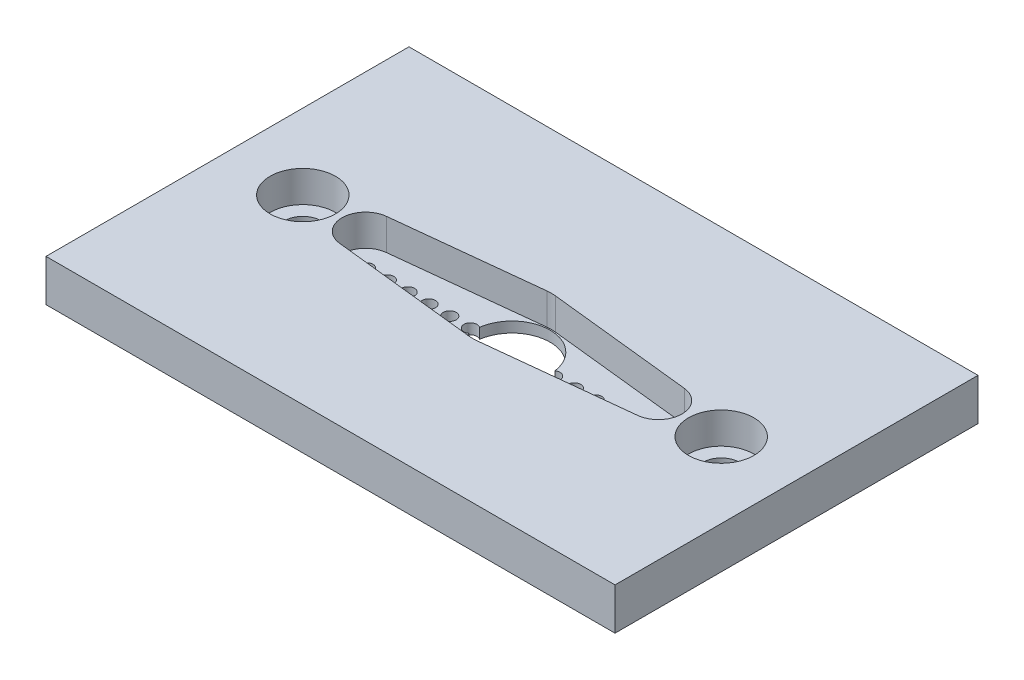
SolidWorks part; units mm, degrees
material "PLA"
ref_plane "Front Plane" through (0, 0, 0) normal (0, 0, 1) x (1, 0, 0)
ref_plane "Top Plane" through (0, 0, 0) normal (0, 1, 0) x (1, 0, 0)
ref_plane "Right Plane" through (0, 0, 0) normal (1, 0, 0) x (0, 0, -1)
sketch "Sketch1" plane through (0, 0, 0) normal (0, 1, 0) x (1, 0, 0)
  line L1 (-27.2, -17.35) -> (27.2, -17.35)
  line L2 (-27.2, -17.35) -> (-27.2, 17.35)
  line L3 (-27.2, 17.35) -> (27.2, 17.35)
  line L4 (27.2, -17.35) -> (27.2, 17.35)
  line L5 (-27.2, -17.35) -> (27.2, 17.35) construction
  line L6 (-27.2, 17.35) -> (27.2, -17.35) construction
  point P0 (0, 0)
  dimension "D1" = 34.7
  dimension "D2" = 54.4
extrude "Boss-Extrude1" add sketch "Sketch1" along normal blind 4
sketch "Sketch2" plane through (0, 4, 0) normal (0, 1, 0) x (1, 0, 0)
  line L0 (-27.2, -17.35) -> (-27.2, 0) construction
  line L2 (-27.2, 17.35) -> (-27.2, -17.35) construction
  line L3 (-27.2, 0) -> (-23.125, 0) construction
  line L4 (-23.125, 0) -> (-23.125, 3.0275) construction
  line L5 (-23.125, 3.0275) -> (-19.2256, 3.0275) construction
  line L6 (-23.125, 0) -> (-23.125, -3.0275) construction
  line L7 (-23.125, -3.0275) -> (-19.2256, -3.0275) construction
  line L8 (0, -55) -> (0, 55) construction
  circle A4 centre (-20, 0) radius 3.125
  circle A5 centre (20, 0) radius 3.125
  dimension "D1" = 4.075
  dimension "D2" = 17.35
  dimension "D3" = 3.0275
  dimension "D4" = 3.8994
  dimension "D5" = 3.8994
  dimension "D6" = 3.0275
extrude "Cut-Extrude1" cut sketch "Sketch2" against normal blind 3
sketch "Sketch7" plane through (0, 1, 0) normal (0, 1, 0) x (1, 0, 0)
  line L0 (0, -2.2) -> (0, 2.2) construction
  circle A0 centre (-20, 0) radius 1.75
  circle A1 centre (20, 0) radius 1.75
extrude "Cut-Extrude5" cut sketch "Sketch7" against normal through all
sketch "Sketch8" plane through (0, 4, 0) normal (0, 1, 0) x (1, 0, 0)
  line L0 (0, 18.9925) -> (0, -21.0066) construction
  line L1 (-3.971, 0.6223) -> (-5.9596, 0.6212) construction
  line L2 (-4.0428, 0) -> (-4.0428, 0.6182) construction
  line L3 (-4.0428, 0.6182) -> (-4.0428, -0.5248) construction
  line L4 (-4.0428, -0.5248) -> (-3.6366, -0.5248) construction
  line L5 (-4.0428, 0.6182) -> (-4.0428, -0.2735) construction
  line L6 (-4.0428, -0.2735) -> (-4.5299, -0.2735) construction
  line L7 (-5.9596, -0.6223) -> (-3.971, -0.6223) construction
  line L8 (-5.3378, -0.0014) -> (-5.9596, 0.6212) construction
  line L9 (-5.9596, 0.6212) -> (-6.5712, -0.1123) construction
  line L10 (5.9596, 0.6212) -> (6.5712, -0.1123) construction
  line L11 (5.3378, -0.0014) -> (5.9596, 0.6212) construction
  line L12 (5.9596, -0.6223) -> (3.971, -0.6223) construction
  line L13 (4.0428, -0.2735) -> (4.5299, -0.2735) construction
  line L14 (3.971, 0.6223) -> (5.9596, 0.6212) construction
  line L15 (0, 0) -> (3.971, 0) construction
  line L16 (4.0428, 0) -> (5.9596, -0.0005) construction
  line L17 (4.0428, 0) -> (5.9596, 0) construction
  line L18 (5.9596, 0) -> (7.9482, 0) construction
  line L19 (7.9482, 0) -> (9.9368, -0.0005) construction
  line L20 (9.9368, -0.0005) -> (11.9254, 0) construction
  line L21 (11.9254, 0) -> (13.914, -0.0005) construction
  arc A2 (-3.6051, -0.5034) -> (3.6051, -0.5034) centre (0, 0) ccw
  arc A3 (-3.6051, 0.5034) -> (-3.6051, -0.5034) centre (-3.971, 0) ccw
  circle A4 centre (-5.9596, -0.0005) radius 0.6218
  circle A5 centre (-5.9596, 0) radius 0.6223
  circle A7 centre (-7.9482, 0) radius 0.6223
  circle A8 centre (-9.9368, -0.0005) radius 0.6218
  circle A11 centre (-11.9254, 0) radius 0.6223
  circle A12 centre (-13.914, -0.0005) radius 0.6218
  circle A13 centre (13.914, -0.0005) radius 0.6218
  circle A14 centre (11.9254, 0) radius 0.6223
  circle A17 centre (9.9368, -0.0005) radius 0.6218
  circle A18 centre (7.9482, 0) radius 0.6223
  circle A20 centre (5.9596, 0) radius 0.6223
  circle A21 centre (5.9596, -0.0005) radius 0.6218
  arc A22 (3.6051, 0.5034) -> (3.6051, -0.5034) centre (3.971, 0) cw
  arc A23 (3.6051, 0.5034) -> (-3.6051, 0.5034) centre (0, 0) ccw
  point P67 (0, 0)
  dimension "D1" = 7.2801
  dimension "D2" = 4.0428
  dimension "D9" = 1.2446
  dimension "D10" = 1.2436
  dimension "D5" = 0.4062
  dimension "D6" = 0.4872
  dimension "D7" = 0.6195
  dimension "D8" = 0.7335
extrude "Cut-Extrude6" cut sketch "Sketch8" against normal through all contours A12 | A11 | A8 | A7 | A4 | A22 A23 A3 A2 | A21 | A17 | A18 | A14 | A13
sketch "Sketch9" plane through (0, 4, 0) normal (0, 1, 0) x (1, 0, 0)
  line L0 (0, 0) -> (-0.4018, 3.7338) construction
  line L1 (0, 0) -> (-14.2411, 2.2371) construction
  line L2 (-14.2411, 2.2371) -> (-0.4018, 3.7338)
  line L3 (0, 0) -> (15.4172, 0) construction
  line L4 (0, 0) -> (0, -14.318) construction
  line L5 (-14.2411, -2.2371) -> (-0.4018, -3.7338)
  line L6 (14.2411, -2.2371) -> (0.4018, -3.7338)
  line L7 (14.2411, 2.2371) -> (0.4018, 3.7338)
  line L8 (-14.2411, 2.2371) -> (-16.201, 0.467) construction
  arc A0 (-0.4018, 3.7338) -> (0.4018, 3.7338) centre (0, 0.0189) cw
  arc A1 (-0.4018, -3.7338) -> (0.4018, -3.7338) centre (0, -0.0189) ccw
  arc A2 (-14.2411, 2.2371) -> (-14.2411, -2.2371) centre (-14, 0) ccw
  arc A3 (14.2411, 2.2371) -> (14.2411, -2.2371) centre (14, 0) cw
  point P16 (0, 0)
  dimension "D1" = 14.2411
  dimension "D2" = 2.2371
  dimension "D3" = 3.7338
  dimension "D4" = 0.4018
  dimension "D5" = 1.9599
  dimension "D6" = 1.7701
extrude "Cut-Extrude7" cut sketch "Sketch9" against normal blind 3
